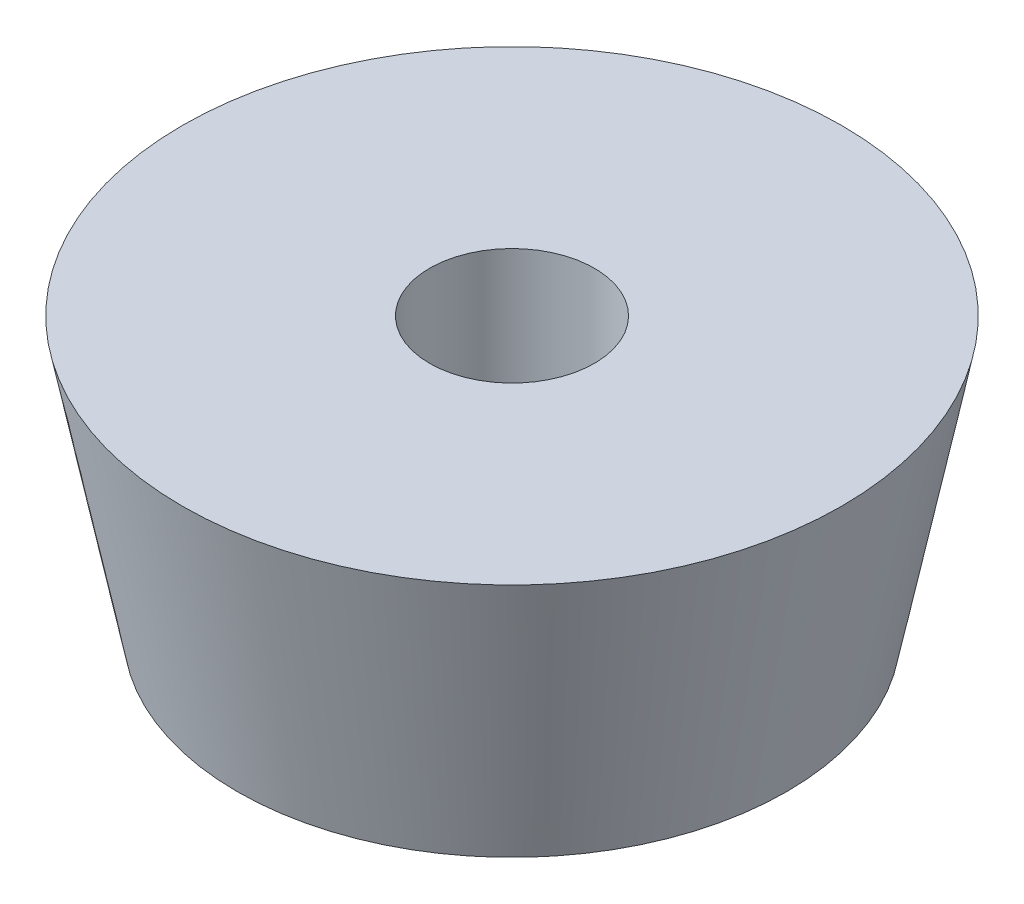
SolidWorks part; units mm, degrees
ref_plane "Front Plane" through (0, 0, 0) normal (0, 0, 1) x (1, 0, 0)
ref_plane "Top Plane" through (0, 0, 0) normal (0, 1, 0) x (1, 0, 0)
ref_plane "Right Plane" through (0, 0, 0) normal (1, 0, 0) x (0, 0, -1)
sketch "Sketch1" plane through (0, 0, 0) normal (0, 0, 1) x (1, 0, 0)
  line L0 (0, 7.9296) -> (0, -5.6267) construction
  line L1 (1.5, 0) -> (5, 0)
  line L2 (5, 0) -> (6, 5)
  line L3 (6, 5) -> (1.5, 5)
  line L4 (1.5, 5) -> (1.5, 0)
  point P5 (0, 0)
  point P8 (0, 0)
  dimension "D1" = 5
  dimension "D2" = 3.5
  dimension "D3" = 101.31
  dimension "D4" = 1.5
revolve "Revolve1" add sketch "Sketch1" angle 360 about L0
